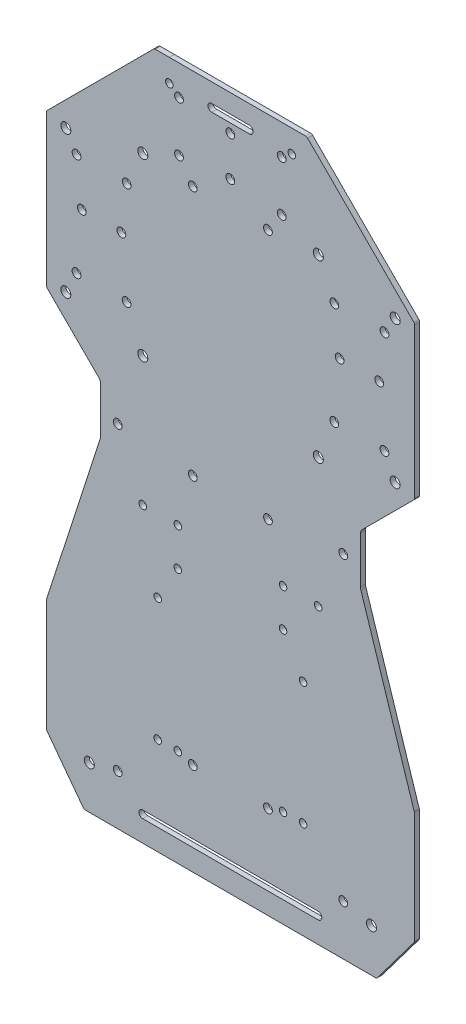
SolidWorks part; units mm, degrees
ref_plane "前视基准面" through (0, 0, 0) normal (0, 0, 1) x (1, 0, 0)
ref_plane "上视基准面" through (0, 0, 0) normal (0, 1, 0) x (1, 0, 0)
ref_plane "右视基准面" through (0, 0, 0) normal (1, 0, 0) x (0, 0, -1)
sketch "Model" plane through (0, 0, 0) normal (0, 0, 1) x (1, 0, 0)
  line L0 (2310.0448, 1913.6863) -> (2310.0617, 1973.7044)
  line L1 (2310.3548, 1974.4114) -> (2352.8062, 2016.8388)
  line L2 (2414.2385, 2016.8214) -> (2456.6658, 1974.3701)
  line L3 (2456.9585, 1973.6629) -> (2456.9416, 1913.6447)
  line L4 (2353.5131, 2017.1315) -> (2359.099, 2017.1315)
  line L5 (2376.0224, 2009.6315) -> (2391.0224, 2009.6315)
  line L6 (2376.0224, 2006.6315) -> (2391.0224, 2006.6315)
  line L7 (2310.3377, 1912.9789) -> (2330.9946, 1892.3219)
  line L8 (2456.6485, 1912.9377) -> (2435.9822, 1892.283)
  line L9 (2331.5804, 1890.9077) -> (2331.5804, 1872.2096)
  line L10 (2310.2446, 1759.9337) -> (2324.7447, 1740.6002)
  line L11 (2435.396, 1890.8695) -> (2435.3859, 1872.17)
  line L12 (2456.655, 1759.8863) -> (2442.1503, 1740.5685)
  line L13 (2325.5445, 1740.2002) -> (2441.3503, 1740.1689)
  line L14 (2331.4346, 1871.2857) -> (2310.0932, 1805.3505)
  line L15 (2310.0446, 1805.0426) -> (2310.0446, 1760.5337)
  line L16 (2435.5311, 1871.2461) -> (2456.832, 1805.3091)
  line L17 (2456.8804, 1805.0012) -> (2456.8553, 1760.4861)
  line L18 (2348.4501, 1751.694) -> (2418.4501, 1751.6751)
  line L19 (2418.4501, 1748.6751) -> (2348.4501, 1748.694)
  line L20 (2359.099, 2017.1315) -> (2413.5315, 2017.1145)
  circle A0 centre (2359.099, 2008.1315) radius 1.5
  circle A1 centre (2407.9457, 2008.1315) radius 1.5
  arc A2 (2376.0224, 2009.6315) -> (2376.0224, 2006.6315) centre (2376.0224, 2008.1315) ccw
  arc A3 (2391.0224, 2006.6315) -> (2391.0224, 2009.6315) centre (2391.0224, 2008.1315) ccw
  circle A4 centre (2348.5016, 1978.6745) radius 2
  circle A5 centre (2348.5016, 1908.6745) radius 2
  circle A6 centre (2418.5431, 1978.6745) radius 2
  circle A7 centre (2418.5431, 1908.6745) radius 2
  circle A8 centre (2412.4712, 1828.0364) radius 1.5
  circle A9 centre (2317.7886, 1972.0459) radius 2
  circle A10 centre (2449.2307, 1972.0088) radius 2
  circle A11 centre (2354.4712, 1828.0364) radius 1.5
  circle A12 centre (2354.4712, 1779.0364) radius 1.5
  circle A13 centre (2412.4712, 1779.0364) radius 1.5
  circle A14 centre (2327.1446, 1757.4004) radius 2
  circle A15 centre (2439.7502, 1757.4004) radius 2
  arc A16 (2418.4493, 1748.6751) -> (2418.4501, 1751.6751) centre (2418.4497, 1750.1751) ccw
  arc A17 (2348.4509, 1751.694) -> (2348.4501, 1748.694) centre (2348.4505, 1750.194) ccw
  arc A18 (2418.4778, 1855.5871) -> (2418.4786, 1858.5871) centre (2418.4786, 1857.0871) ccw
  arc A19 (2348.4794, 1858.6061) -> (2348.4786, 1855.6061) centre (2348.4786, 1857.1061) ccw
  circle A20 centre (2317.7726, 1915.3403) radius 2
  circle A21 centre (2449.2074, 1915.2863) radius 2
  circle A22 centre (2348.4786, 1857.1061) radius 1.5
  circle A23 centre (2418.4786, 1857.0871) radius 1.5
  circle A24 centre (2362.4786, 1857.1023) radius 1.5
  circle A25 centre (2404.4786, 1857.0911) radius 1.5
  arc A26 (2414.2385, 2016.8214) -> (2413.5315, 2017.1145) centre (2413.5312, 2016.1145) ccw
  arc A27 (2353.5131, 2017.1315) -> (2352.8062, 2016.8388) centre (2353.5131, 2016.1315) ccw
  arc A28 (2310.3548, 1974.4114) -> (2310.0617, 1973.7044) centre (2311.0617, 1973.7041) ccw
  arc A29 (2456.9585, 1973.6629) -> (2456.6658, 1974.3701) centre (2455.9585, 1973.6632) ccw
  arc A30 (2310.0448, 1913.6863) -> (2310.3377, 1912.9789) centre (2311.0448, 1913.686) ccw
  arc A31 (2456.6485, 1912.9377) -> (2456.9416, 1913.6447) centre (2455.9416, 1913.645) ccw
  arc A32 (2331.5804, 1890.9077) -> (2330.9946, 1892.3219) centre (2329.5804, 1890.9077) ccw
  arc A33 (2435.9822, 1892.283) -> (2435.396, 1890.8695) centre (2437.396, 1890.8684) ccw
  arc A34 (2331.4346, 1871.2857) -> (2331.5804, 1872.2096) centre (2328.5804, 1872.2096) ccw
  arc A35 (2435.3859, 1872.17) -> (2435.5311, 1871.2461) centre (2438.3859, 1872.1684) ccw
  arc A36 (2310.0932, 1805.3505) -> (2310.0446, 1805.0426) centre (2311.0446, 1805.0426) ccw
  arc A37 (2456.8804, 1805.0012) -> (2456.832, 1805.3091) centre (2455.8804, 1805.0017) ccw
  arc A38 (2310.0446, 1760.5337) -> (2310.2446, 1759.9337) centre (2311.0446, 1760.5337) ccw
  arc A39 (2456.655, 1759.8863) -> (2456.8553, 1760.4861) centre (2455.8553, 1760.4867) ccw
  arc A40 (2441.3503, 1740.1689) -> (2442.1503, 1740.5685) centre (2441.3506, 1741.1689) ccw
  arc A41 (2324.7447, 1740.6002) -> (2325.5445, 1740.2002) centre (2325.5447, 1741.2002) ccw
  spline S0 degree 3 poles (0, 0) (0.3333, 0) (0.6667, 0) (1, 0) knots 0 0 0 0 1 1 1 1
extrude "凸台-拉伸1" add sketch "Model" along normal blind 2 contours L10 A41 L13 A40 L12 A39 L17 A37 L16 A35 L11 A33 L8 A31 L3 A29 L2 A26 L20 L4 A27 L1 A28 L0 A30 L7 A32 L9 A34 L14 A36 L15 A38 A0 A1 A3 L6 A2 L5 A4 A5 A6 A7
sketch "草图1" plane through (0, 0, 0) normal (0, 0, -1) x (-1, 0, 0)
  circle A0 centre (-2404.4712, 1842.0364) radius 1.5
  circle A1 centre (-2362.4712, 1842.0364) radius 1.5
  circle A2 centre (-2362.4712, 1779.0364) radius 1.5
  circle A3 centre (-2404.4712, 1779.0364) radius 1.5
extrude "切除-拉伸1" cut sketch "草图1" against normal blind 2
sketch "草图2" plane through (0, 0, 0) normal (0, 0, -1) x (-1, 0, 0)
  line L0 (-2325.5445, 1740.2002) -> (-2441.3503, 1740.1689) construction
  line L2 (-2383.5101, 1973.6837) -> (-2383.5101, 1701.7365) construction
  circle A0 centre (-2428.5101, 1880.1724) radius 1.75
  circle A1 centre (-2338.5101, 1880.1724) radius 1.75
  circle A2 centre (-2428.5101, 1760.1724) radius 1.75
  circle A3 centre (-2338.5101, 1760.1724) radius 1.75
  arc A4 (-2418.4501, 1751.6751) -> (-2418.4501, 1748.6751) centre (-2418.4497, 1750.1751) ccw construction
  dimension "D6" = 3.5
  dimension "D7" = 3.5
  dimension "D8" = 3.5
  dimension "D9" = 3.5
  dimension "D10" = 34.9396
  dimension "D1" = 90
  dimension "D2" = 90
  dimension "D3" = 120
  dimension "D4" = 120
  dimension "D5" = 20
  dimension "D11" = 45
  dimension "D12" = 45
  dimension "D13" = 120
extrude "切除-拉伸2" cut sketch "草图2" against normal blind 10
sketch "草图3" plane through (0, 0, 0) normal (0, 0, -1) x (-1, 0, 0)
  line L0 (-2383.4501, 1751.6846) -> (-2383.4501, 2152.2623) construction
  line L1 (-2348.4501, 1751.694) -> (-2418.4501, 1751.6751) construction
  line L2 (-2456.9585, 1973.6629) -> (-2456.9416, 1913.6447) construction
  line L3 (-2310.0448, 1913.6863) -> (-2310.0617, 1973.7044) construction
  line L4 (-2359.099, 2017.1315) -> (-2413.5315, 2017.1145) construction
  circle A0 centre (-2444.9561, 1965.0088) radius 1.75
  circle A1 centre (-2424.9561, 1965.0088) radius 1.75
  circle A2 centre (-2444.9445, 1924.0088) radius 1.75
  circle A3 centre (-2424.9445, 1924.0088) radius 1.75
  circle A4 centre (-2403.9501, 2005.1175) radius 1.75
  circle A5 centre (-2362.9501, 2005.1303) radius 1.75
  circle A6 centre (-2403.9501, 1985.1175) radius 1.75
  circle A7 centre (-2362.9501, 1985.1303) radius 1.75
  circle A8 centre (-2342.0592, 1965.0088) radius 1.75
  circle A9 centre (-2322.0592, 1965.0088) radius 1.75
  circle A10 centre (-2342.0477, 1924.0088) radius 1.75
  circle A11 centre (-2322.0477, 1924.0088) radius 1.75
  circle A12 centre (-2449.2307, 1972.0088) radius 2 construction
  circle A13 centre (-2442.8561, 1947.0088) radius 1.75
  circle A14 centre (-2427.0561, 1947.0088) radius 1.75
  circle A15 centre (-2339.9592, 1947.0088) radius 1.75
  circle A16 centre (-2324.1592, 1947.0088) radius 1.75
  circle A17 centre (-2383.4501, 2003.0175) radius 1.75
  circle A18 centre (-2383.4501, 1987.2175) radius 1.75
  dimension "D1" = 3.5
  dimension "D2" = 3.5
  dimension "D3" = 3.5
  dimension "D4" = 3.5
  dimension "D5" = 3.5
  dimension "D6" = 3.5
  dimension "D7" = 3.5
  dimension "D8" = 3.5
  dimension "D9" = 3.5
  dimension "D10" = 3.5
  dimension "D11" = 3.5
  dimension "D12" = 3.5
  dimension "D33" = 7
  dimension "D34" = 0
  dimension "D37" = 3.5
  dimension "D38" = 3.5
  dimension "D43" = 3.5
  dimension "D44" = 3.5
  dimension "D49" = 3.5
  dimension "D50" = 3.5
  dimension "D13" = 20
  dimension "D14" = 20
  dimension "D15" = 20
  dimension "D16" = 20
  dimension "D17" = 20
  dimension "D18" = 20
  dimension "D19" = 41
  dimension "D20" = 41
  dimension "D21" = 41
  dimension "D22" = 41
  dimension "D23" = 41
  dimension "D24" = 41
  dimension "D25" = 12
  dimension "D26" = 12
  dimension "D27" = 12
  dimension "D28" = 12
  dimension "D29" = 12
  dimension "D30" = 12
  dimension "D31" = 20.5
  dimension "D32" = 20.5
  dimension "D35" = 0
  dimension "D36" = 0
  dimension "D39" = 15.8
  dimension "D40" = 2.1
  dimension "D41" = 18
  dimension "D42" = 18
  dimension "D45" = 15.8
  dimension "D46" = 2.1
  dimension "D47" = 18
  dimension "D48" = 18
  dimension "D51" = 15.8
  dimension "D52" = 2.1
extrude "切除-拉伸3" cut sketch "草图3" against normal blind 10
sketch "草图4" plane through (0, 0, 0) normal (0, 0, -1) x (-1, 0, 0)
  line L0 (-2348.4501, 1751.694) -> (-2418.4501, 1751.6751) construction
  line L1 (-2383.4501, 1751.6846) -> (-2383.4501, 2087.9551) construction
  circle A0 centre (-2398.4501, 1977.1805) radius 1.75
  circle A1 centre (-2398.4501, 1877.1805) radius 1.75
  circle A2 centre (-2398.4501, 1777.1805) radius 1.75
  circle A3 centre (-2368.4501, 1977.1886) radius 1.75
  circle A4 centre (-2368.4501, 1877.1886) radius 1.75
  circle A5 centre (-2368.4501, 1777.1886) radius 1.75
  dimension "D1" = 3.5
  dimension "D2" = 3.5
  dimension "D3" = 3.5
  dimension "D4" = 3.5
  dimension "D5" = 3.5
  dimension "D6" = 3.5
  dimension "D7" = 100
  dimension "D8" = 100
  dimension "D9" = 100
  dimension "D10" = 100
  dimension "D11" = 25.5
  dimension "D12" = 25.5
  dimension "D13" = 30
  dimension "D14" = 15
  dimension "D15" = 30
  dimension "D16" = 15
  dimension "D17" = 30
  dimension "D18" = 15
extrude "切除-拉伸4" cut sketch "草图4" against normal blind 10
